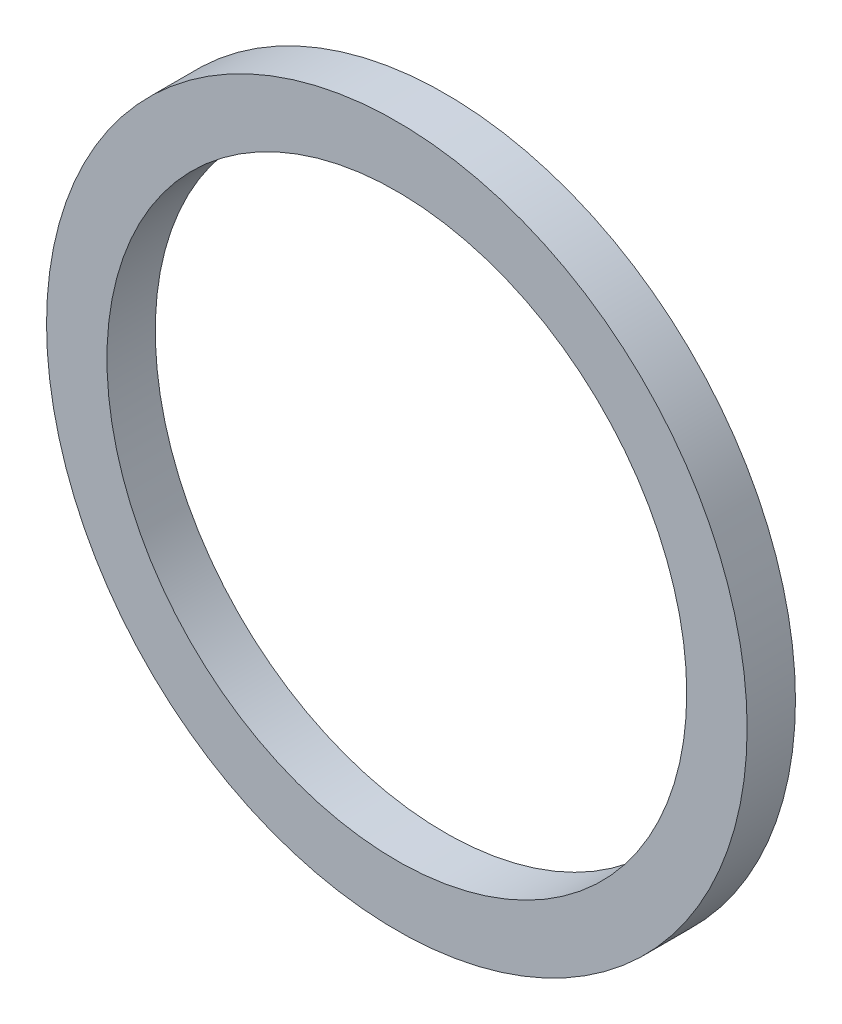
SolidWorks part; units mm, degrees
ref_plane "Front Plane" through (0, 0, 0) normal (0, 0, 1) x (1, 0, 0)
ref_plane "Top Plane" through (0, 0, 0) normal (0, 1, 0) x (1, 0, 0)
ref_plane "Right Plane" through (0, 0, 0) normal (1, 0, 0) x (0, 0, -1)
sketch "Sketch1" plane through (0, 0, 0) normal (0, 0, 1) x (1, 0, 0)
  circle A0 centre (0, 0) radius 72.5
  circle A1 centre (0, 0) radius 60
  point P5 (0, 1.8032)
  dimension "D1" = 145
  dimension "D2" = 120
extrude "Boss-Extrude1" add sketch "Sketch1" along normal blind 10
equation "\"smallPulleyTeeth\"= 15"
equation "\"largePulleyTeeth\"= 30"
equation "\"eighthThick\"= 2.9mm"
equation "\"sixteenthThick\" = 1.7mm"
equation "\"quarterThick\"=5.9mm"
equation "\"OD\" = 145mm"
equation "\"puckAngle\" = 60.5deg"
equation "\"puckDiam\" = 76.5mm"
equation "\"axlePress\" = 5.9mm"
equation "\"press\" = 0.2mm"
equation "\"wheelClear\" = 0.3mm"
equation "\"10-32clear\" = 4.5mm"
equation "\"6-32clear\" = 3.3mm"
equation "\"8-32clear\" = 4.0mm"
equation "\"wheelHeight\" = 24mm"
equation "\"wheelWell\" = 62mm"
equation "\"D1@Sketch1\"=\"OD\""
